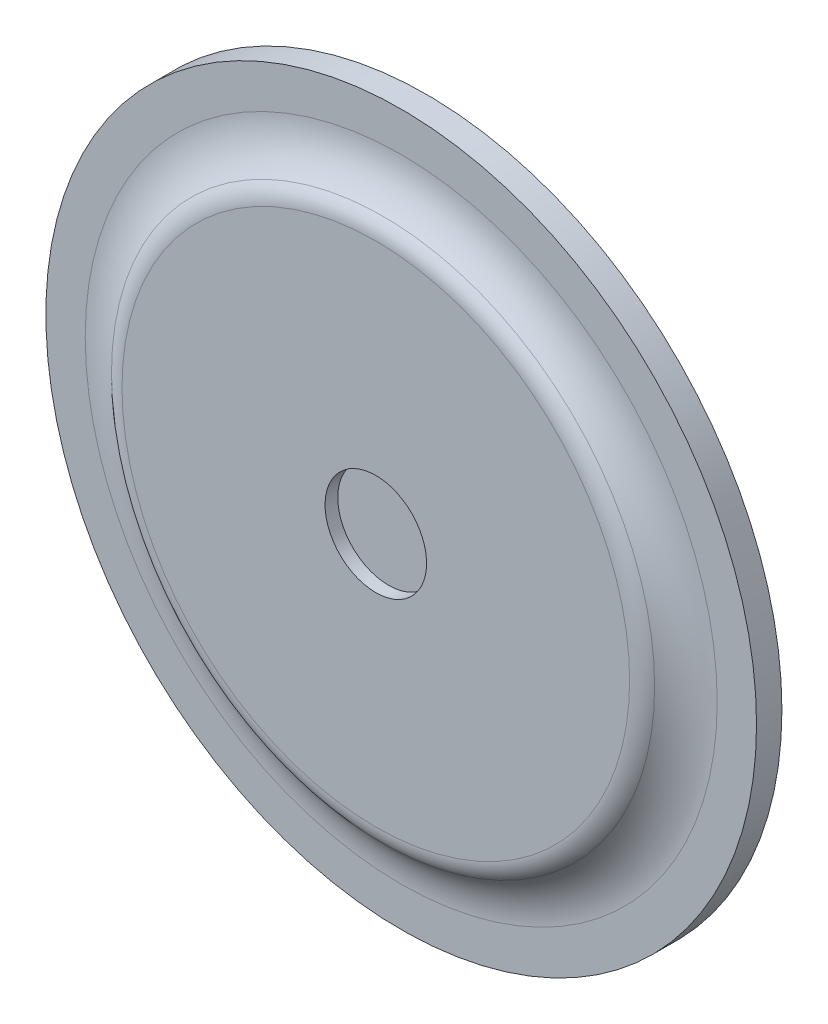
SolidWorks part; units mm, degrees
ref_plane "Front Plane" through (0, 0, 0) normal (0, 0, 1) x (1, 0, 0)
ref_plane "Top Plane" through (0, 0, 0) normal (0, 1, 0) x (1, 0, 0)
ref_plane "Right Plane" through (0, 0, 0) normal (1, 0, 0) x (0, 0, -1)
sketch "Sketch1" plane through (0, 0, 0) normal (1, 0, 0) x (0, 0, -1)
  line L1 (-21.59, 26.9875) -> (-21.59, 0)
  line L2 (0, 0) -> (87.2706, 0) construction
  line L6 (-31.75, 31.75) -> (-31.75, 0)
  line L7 (-31.75, 0) -> (-21.59, 0)
  line L10 (-28.575, 39.5271) -> (-28.575, 44.45)
  line L11 (-28.575, 44.45) -> (-25.4, 44.45)
  line L13 (49.6911, 31.75) -> (-25.4, 31.75) construction
  line L14 (-25.4, 44.45) -> (-25.4, 26.9875)
  line L15 (-25.4, 31.75) -> (-25.4, -31.75) construction
  line L16 (-25.4, 26.9875) -> (-21.59, 26.9875)
  arc A1 (-28.575, 39.5271) -> (-30.8429, 33.972) centre (-36.5125, 39.5271) cw
  arc A2 (-31.75, 31.75) -> (-30.8429, 33.972) centre (-28.575, 31.75) cw
  point P12 (-31.75, 31.75)
  dimension "D3" = 12.7
  dimension "D5" = 3.175
  dimension "D7" = 7.9375
  dimension "D2" = 10.16
  dimension "D4" = 3.175
revolve "Revolve1" add sketch "Sketch1" angle 360 about L7
sketch "Sketch2" plane through (0, 0, 0) normal (1, 0, 0) x (0, 0, -1)
  line L3 (-25.4, 26.9875) -> (-21.59, 26.9875) construction
  line L4 (-31.75, 31.75) -> (-31.75, 0) construction
  line L5 (-21.59, 26.9875) -> (-21.59, 0) construction
  line L6 (-21.59, 26.9875) -> (-21.59, 0) construction
  line L7 (-30.1625, 25.4) -> (-23.1775, 25.4)
  line L8 (-30.1625, 31.75) -> (-30.1625, 0)
  line L9 (-30.1625, 25.4) -> (-30.1625, 6.35)
  line L10 (-23.1775, 25.4) -> (-23.1775, 0)
  line L11 (-31.75, 0) -> (-23.1775, 0)
  line L12 (-31.7498, 25.4) -> (-23.1775, 25.4) construction
  line L13 (-30.1625, 6.35) -> (-31.75, 6.35)
  line L15 (0, 0) -> (87.2706, 0) construction
  line L16 (-31.75, 6.35) -> (-31.75, 0)
  line L18 (-31.7498, 26.9875) -> (-21.59, 26.9875) construction
  dimension "D3" = 6.35
  dimension "D4" = 1.5875
  dimension "D1" = 1.5875
  dimension "D2" = 1.5875
revolve "Cut-Revolve1" cut sketch "Sketch2" angle 360 about L11
sketch "Sketch3" plane through (0, 0, 21.59) normal (0, 0, -1) x (-1, 0, 0)
  line L0 (0, 31.75) -> (0, 0) construction
  circle A0 centre (0, 3.175) radius 0.7938
  circle A1 centre (2.7496, 1.5875) radius 0.7938
  circle A2 centre (2.7496, -1.5875) radius 0.7938
  circle A3 centre (0, -3.175) radius 0.7937
  circle A4 centre (-2.7496, -1.5875) radius 0.7938
  circle A5 centre (-2.7496, 1.5875) radius 0.7938
  point P17 (0, 0)
  dimension "D1" = 1.5875
  dimension "D2" = 3.175
  dimension "D3" = 6
extrude "Cut-Extrude1" cut sketch "Sketch3" against normal up to surface (1.5875 mm away) up to face at (0, -25.4, 23.1775)
